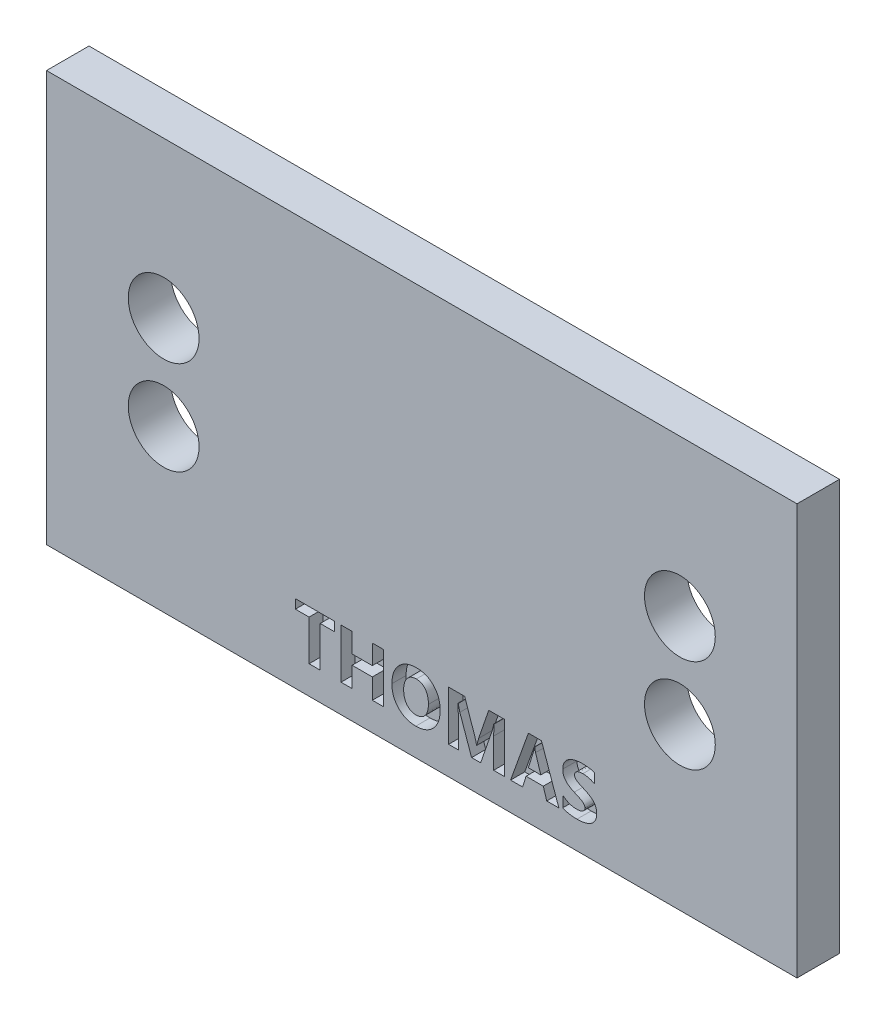
SolidWorks part; units mm, degrees
ref_plane "Front Plane" through (0, 0, 0) normal (0, 0, 1) x (1, 0, 0)
ref_plane "Top Plane" through (0, 0, 0) normal (0, 1, 0) x (1, 0, 0)
ref_plane "Right Plane" through (0, 0, 0) normal (1, 0, 0) x (0, 0, -1)
sketch "Sketch1" plane through (0, 0, 0) normal (0, 0, 1) x (1, 0, 0)
  line L0 (0.8421, 18.4079) -> (0.8421, -10.5921) construction
  line L1 (-25.6579, 18.4079) -> (27.3421, 18.4079)
  line L2 (-25.6579, 18.4079) -> (-25.6579, -10.5921)
  line L3 (-25.6579, -10.5921) -> (27.3421, -10.5921)
  line L4 (27.3421, 18.4079) -> (27.3421, -10.5921)
  circle A0 centre (-17.3867, 0.7813) radius 2.5
  circle A1 centre (19.0709, 0.7813) radius 2.5
  circle A2 centre (19.0709, 7.3999) radius 2.5
  circle A3 centre (-17.3867, 7.3999) radius 2.5
  point P14 (-17.3867, -8.299)
  point P15 (-17.3867, 0.7813)
  dimension "D3" = 5
  dimension "D1" = 53
  dimension "D2" = 29
extrude "Boss-Extrude1" add sketch "Sketch1" along normal blind 3
sketch "Sketch2" plane through (0, 0, 3) normal (0, 0, 1) x (1, 0, 0)
  text T0 "THOMAS" font "Gadugi" height 3.5
extrude "Cut-Extrude1" cut sketch "Sketch2" against normal blind 1
